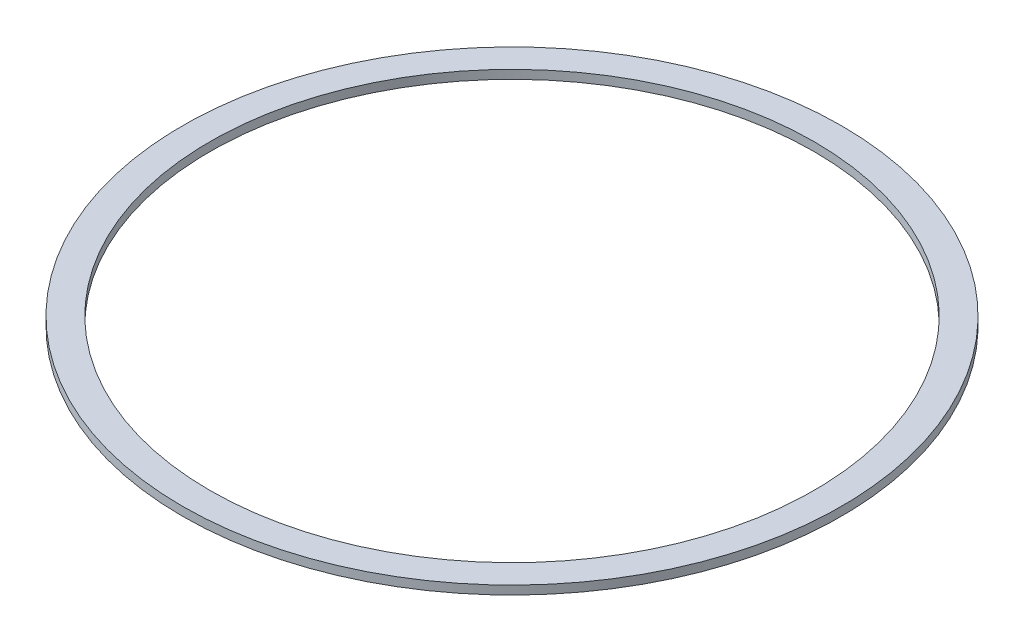
SolidWorks part; units mm, degrees
ref_plane "Front Plane" through (0, 0, 0) normal (0, 0, 1) x (1, 0, 0)
ref_plane "Top Plane" through (0, 0, 0) normal (0, 1, 0) x (1, 0, 0)
ref_plane "Right Plane" through (0, 0, 0) normal (1, 0, 0) x (0, 0, -1)
sketch "Sketch1" plane through (0, 0, 0) normal (0, 1, 0) x (1, 0, 0)
  circle A0 centre (0, 0) radius 76.2
  circle A1 centre (0, 0) radius 69.85
  dimension "D1" = 152.4
  dimension "D2" = 139.7
extrude "Boss-Extrude1" add sketch "Sketch1" along normal blind 2
